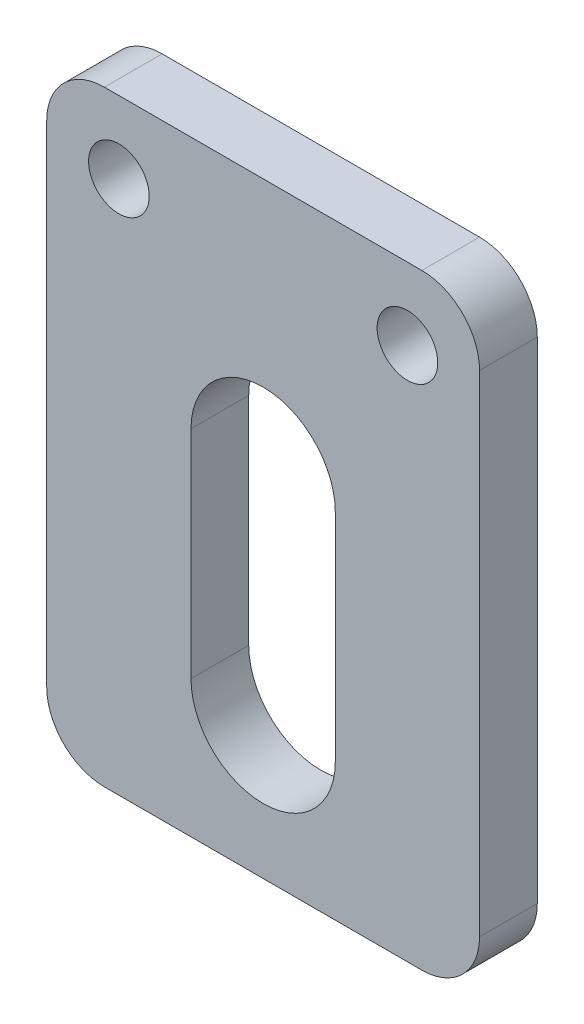
SolidWorks part; units mm, degrees
ref_plane "前视基准面" through (0, 0, 0) normal (0, 0, 1) x (1, 0, 0)
ref_plane "上视基准面" through (0, 0, 0) normal (0, 1, 0) x (1, 0, 0)
ref_plane "右视基准面" through (0, 0, 0) normal (1, 0, 0) x (0, 0, -1)
other "Configuration Table"
sketch "草图1" plane through (0, 0, 0) normal (0, 0, 1) x (1, 0, 0)
  line L1 (0, 0) -> (30, 0)
  line L2 (0, 0) -> (0, -42)
  line L3 (0, -42) -> (30, -42)
  line L4 (30, 0) -> (30, -42)
  dimension "D1" = 30
  dimension "D2" = 42
extrude "凸台-拉伸1" add sketch "草图1" along normal blind 4
sketch "草图2" plane through (0, 0, 4) normal (0, 0, 1) x (1, 0, 0)
  line L0 (30, 0) -> (0, 0) construction
  line L7 (15, -17.5) -> (15, -32.5) construction
  line L8 (20, -17.5) -> (20, -32.5)
  line L9 (10, -17.5) -> (10, -32.5)
  line L10 (30, -42) -> (30, 0) construction
  line L11 (0, 0) -> (0, -42) construction
  line L12 (0, 0) -> (0, -42) construction
  arc A0 (20, -17.5) -> (10, -17.5) centre (15, -17.5) ccw
  arc A1 (10, -32.5) -> (20, -32.5) centre (15, -32.5) ccw
  circle A2 centre (5, -5) radius 2.1
  circle A3 centre (25, -5) radius 2.1
  point P12 (15, -25)
  dimension "D6" = 5
  dimension "D8" = 4.2
  dimension "D9" = 4.2
  dimension "D2" = 15
  dimension "D3" = 5
  dimension "D4" = 5
  dimension "D5" = 25
  dimension "D7" = 15
  dimension "D11" = 5
  dimension "D12" = 5
extrude "切除-拉伸1" cut sketch "草图2" against normal through all
fillet "圆角1" radius 4 4 edges at (0, -42, 2) (30, -42, 2) (30, 0, 2) (0, 0, 2)
